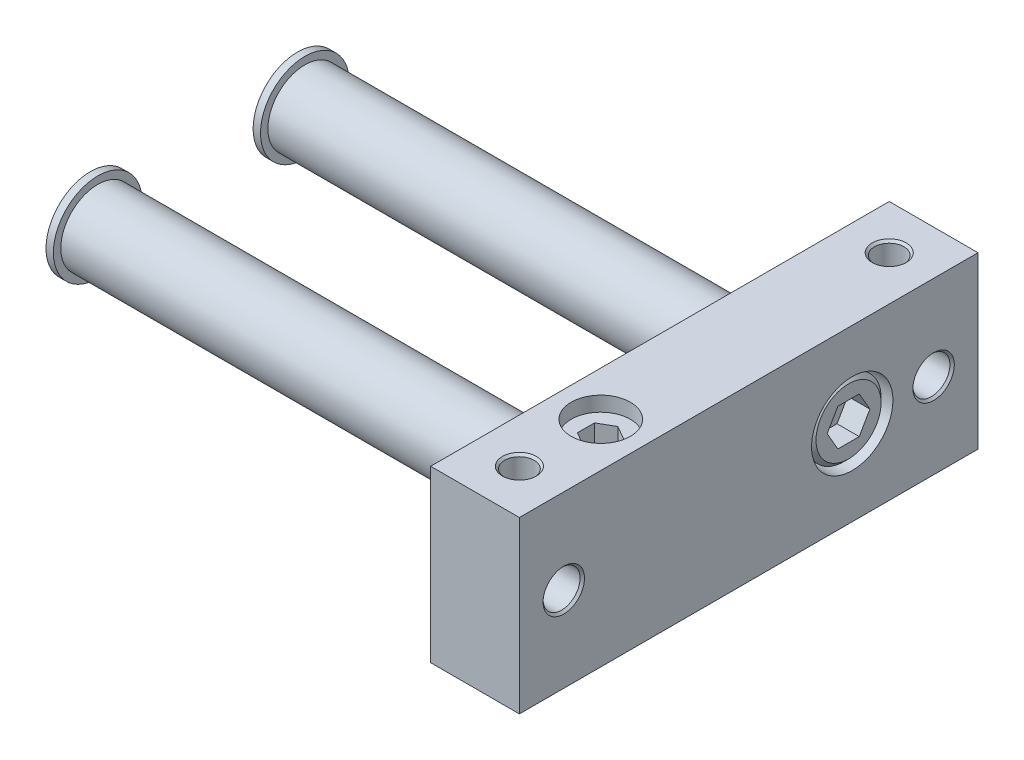
SolidWorks part; units mm, degrees
ref_plane "Plane1" through (0, 0, 0) normal (0, 0, 1) x (1, 0, 0)
ref_plane "Plane2" through (0, 0, 0) normal (0, 1, 0) x (1, 0, 0)
ref_plane "Plane3" through (0, 0, 0) normal (1, 0, 0) x (0, 0, -1)
sketch "Plate_Sketch" plane through (0, 0, 0) normal (1, 0, 0) x (0, 0, -1)
  line L0 (-31, 11.5) -> (-31, -11.5)
  line L1 (-31, -11.5) -> (31, -11.5)
  line L2 (31, -11.5) -> (31, 11.5)
  line L3 (31, 11.5) -> (-31, 11.5)
  line L4 (-24.2, 0) -> (24.2, 0) construction
  line L5 (0, -6.75) -> (0, 9.75) construction
  line L6 (0, 12.5779) -> (0, -12.5779) construction
  line L7 (16.4357, 0) -> (-16.4357, 0) construction
  dimension "C" = 62
  dimension "D" = 23
extrude "Plate" add sketch "Plate_Sketch" along normal blind 12
hole_wizard "Tapped Hole Face" positions "Tapped Hole Face Loc" profile "Tapped Hole Face Profile" tap size "M3x0.5" standard "Ansi Metric" end condition through all
sketch "Tapped Hole Face Loc" plane through (12, 0, 0) normal (1, 0, 0) x (0, 0, -1)
  line L0 (0, 0) -> (0, 21.0226) construction
  line L1 (-31, -11.5) -> (31, -11.5) construction
  point P0 (-25, 0)
  point P1 (25, 0)
  dimension "G" = 50
  dimension "E" = 11.5
sketch "Tapped Hole Face Profile" plane through (12, 0, 25) normal (0, 1, 0) x (0, 0, -1)
  line L0 (0, 0) -> (0, 12)
  line L1 (0, 12) -> (2.5, 12)
  line L2 (2.5, 12) -> (2.5, 0.3)
  line L3 (2.5, 0.3) -> (2.8, 0)
  line L5 (2.8, 0) -> (0, 0)
  line L6 (-2.5, 0.3) -> (-2.8, 0) construction
  line L11 (0, -6.35) -> (0, 107.95) construction
  dimension "Thread Major Dia." = 5
  dimension "Thru Tap Drill Depth" = 12
  dimension "Near CSink Dia." = 5.6
  dimension "Near CSink Angle" = 90
ref_plane "bottom" through (0, -12.5, 0) normal (0, -1, 0) x (1, 0, 0)
ref_plane "innerlimit" through (-12, 0, 0) normal (1, 0, 0) x (0, 0, -1)
ref_plane "strokelimit" through (-52, 0, 0) normal (1, 0, 0) x (0, 0, -1)
sketch "Rods_Sketch" plane through (-12, 0, 0) normal (-1, 0, 0) x (0, 0, 1)
  line L0 (0, -7.7893) -> (0, 7.4105) construction
  line L1 (0, -12.5779) -> (0, 12.5779) construction
  line L3 (-4, -12.5) -> (4, -12.5) construction
  circle A0 centre (-14, 0) radius 5
  circle A1 centre (14, 0) radius 5
  dimension "NN" = 10
  dimension "H" = 28
  dimension "QQ" = 12.5
extrude "Rods" add sketch "Rods_Sketch" along normal blind 50 and the other way up to surface (24 mm away)
sketch "Piston_Sketch" plane through (-62, 0, 0) normal (-1, 0, 0) x (0, 0, 1)
  circle A0 centre (-14, 0) radius 6
  circle A1 centre (14, 0) radius 6
extrude "Piston" add sketch "Piston_Sketch" along normal blind 1
hole_wizard "Tapped Holes Top" positions "Tapped Holes Top Loc" profile "Tapped Holes Top Profile" tap size "M3x0.5" standard "Ansi Metric"
sketch "Tapped Holes Top Loc" plane through (0, 11.5, 0) normal (0, 1, 0) x (-1, 0, 0)
  line L0 (0, 0) -> (-11.3574, 0) construction
  line L2 (-12, -31) -> (-12, 31) construction
  line L3 (0, -25) -> (-11.7, -25) construction
  point P0 (-6, -25)
  point P1 (-6, 25)
  dimension "I" = 6
sketch "Tapped Holes Top Profile" plane through (6, 11.5, -25) normal (1, 0, 0) x (0, 0, 1)
  line L0 (0, 0) -> (0, 6.4998)
  line L1 (0, 6.4998) -> (1.7, 6.2)
  line L2 (1.7, 6.2) -> (1.7, 6)
  line L3 (1.7, 6) -> (2, 6)
  line L5 (2, 6) -> (2, 0.3)
  line L6 (2, 0.3) -> (2.3, 0)
  line L7 (2.3, 0) -> (0, 0)
  line L8 (-2, 0.3) -> (-2.3, 0) construction
  line L10 (0, 6.4998) -> (-1.7, 6.2) construction
  line L11 (0, -6.35) -> (0, 107.95) construction
  dimension "Tap Drill Dia." = 3.4
  dimension "Tap Drill Depth" = 6.2
  dimension "Thread Major Dia." = 4
  dimension "Thread Depth" = 6
  dimension "Near C'Sink Dia." = 4.6
  dimension "Near C'Sink Angle" = 90
  dimension "Drill Angle" = 160
mirror "Tapped Holes Top Mirror" about plane through (0, 0, 0) normal (0, 1, 0) of "Tapped Holes Top"
sketch "SHCS Seat_Sketch" plane through (12, 0, 0) normal (1, 0, 0) x (0, 0, -1)
  circle A0 centre (14, 0) radius 5.5
  circle A1 centre (14, 0) radius 5 construction
  dimension "Dia" = 11
extrude "SHCS Seat" cut sketch "SHCS Seat_Sketch" against normal blind 6.5
sketch "SHCS Head_Sketch" plane through (5.5, 0, 0) normal (1, 0, 0) x (0, 0, -1)
  circle A0 centre (14, 0) radius 5
  circle A1 centre (14, 0) radius 5.5 construction
  dimension "Dia" = 10
extrude "SHCS Head" add sketch "SHCS Head_Sketch" along normal blind 6
sketch "SHCS Hex_Sketch" plane through (11.5, 0, 0) normal (1, 0, 0) x (0, 0, -1)
  line L1 (15.4434, -2.5) -> (16.8868, 0)
  line L2 (16.8868, 0) -> (15.4434, 2.5)
  line L3 (15.4434, 2.5) -> (12.5566, 2.5)
  line L4 (12.5566, 2.5) -> (11.1132, 0)
  line L5 (11.1132, 0) -> (12.5566, -2.5)
  line L6 (12.5566, -2.5) -> (15.4434, -2.5)
  circle A0 centre (14, 0) radius 2.5 construction
  circle A1 centre (14, 0) radius 5 construction
  dimension "Flats" = 5
extrude "SHCS Hex" cut sketch "SHCS Hex_Sketch" against normal blind 3
chamfer "SHCS Cham" distance 0.6 1 edges at (11.5, 0, -19)
sketch "SS Seat_Sketch" plane through (0, 11.5, 0) normal (0, 1, 0) x (-1, 0, 0)
  line L0 (62, 14) -> (0, 14) construction
  circle A0 centre (-6, 14) radius 4
  dimension "Dia" = 8
extrude "SS Seat" cut sketch "SS Seat_Sketch" against normal blind 2
sketch "SS Hex_Sketch" plane through (0, 9.5, 0) normal (0, 1, 0) x (-1, 0, 0)
  line L1 (-8, 12.8453) -> (-6, 11.6906)
  line L2 (-6, 11.6906) -> (-4, 12.8453)
  line L3 (-4, 12.8453) -> (-4, 15.1547)
  line L4 (-4, 15.1547) -> (-6, 16.3094)
  line L5 (-6, 16.3094) -> (-8, 15.1547)
  line L6 (-8, 15.1547) -> (-8, 12.8453)
  circle A0 centre (-6, 14) radius 2 construction
  circle A1 centre (-6, 14) radius 4 construction
  dimension "Flats" = 4
extrude "SS Hex" cut sketch "SS Hex_Sketch" against normal blind 4
